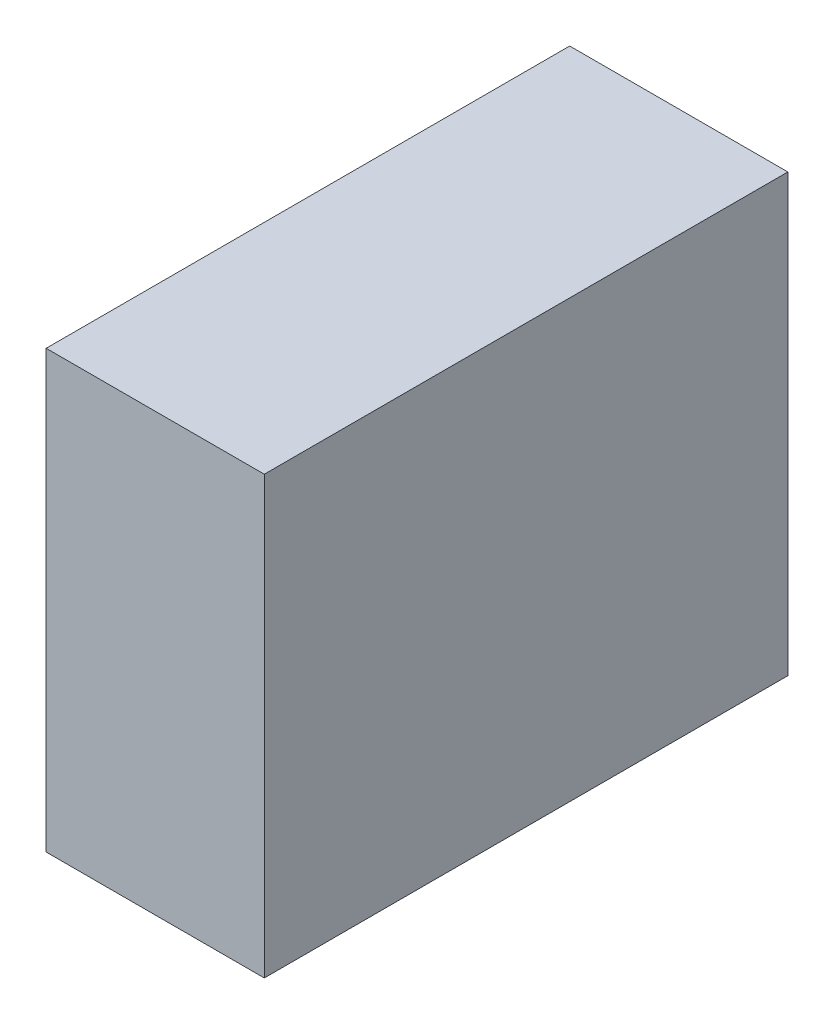
SolidWorks part; units mm, degrees
ref_plane "Front Plane" through (0, 0, 0) normal (0, 0, 1) x (1, 0, 0)
ref_plane "Top Plane" through (0, 0, 0) normal (0, 1, 0) x (1, 0, 0)
ref_plane "Right Plane" through (0, 0, 0) normal (1, 0, 0) x (0, 0, -1)
other "Configuration Table"
sketch "Sketch1" plane through (0, 0, 0) normal (0, 0, 1) x (1, 0, 0)
  line L1 (300, 200) -> (350, 200)
  line L2 (300, 200) -> (300, 300)
  line L3 (300, 300) -> (350, 300)
  line L4 (350, 200) -> (350, 300)
extrude "OVEN_pano_surucu_mentese_1_1" add sketch "Sketch1" against normal blind 120 from offset 128 separate body
